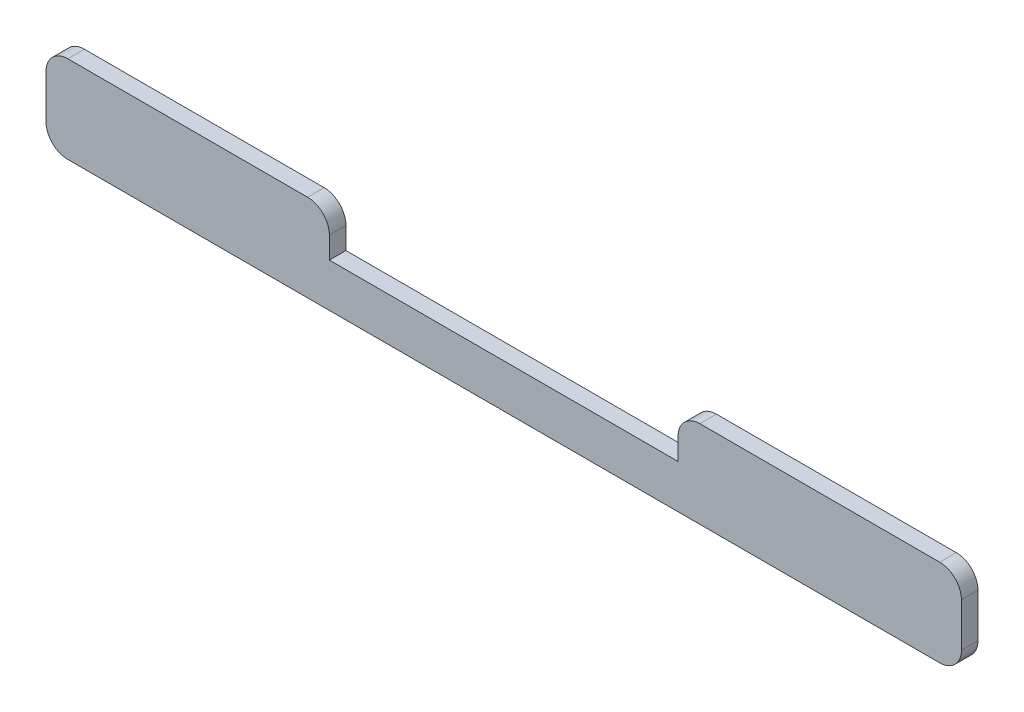
SolidWorks part; units mm, degrees
ref_plane "Front Plane" through (0, 0, 0) normal (0, 0, 1) x (1, 0, 0)
ref_plane "Top Plane" through (0, 0, 0) normal (0, 1, 0) x (1, 0, 0)
ref_plane "Right Plane" through (0, 0, 0) normal (1, 0, 0) x (0, 0, -1)
sketch "Sketch1" plane through (0, 0, 0) normal (0, 0, 1) x (1, 0, 0)
  line L1 (6.35, 0) -> (260.35, 0)
  line L2 (0, 6.35) -> (0, 19.05)
  line L3 (190.5, 25.4) -> (260.35, 25.4)
  line L4 (266.7, 6.35) -> (266.7, 19.05)
  line L5 (82.55, 12.7) -> (184.15, 12.7)
  line L6 (82.55, 12.7) -> (82.55, 19.05)
  line L7 (6.35, 25.4) -> (76.2, 25.4)
  line L8 (184.15, 12.7) -> (184.15, 19.05)
  line L11 (82.55, 12.7) -> (82.55, 19.05)
  arc A0 (260.35, 25.4) -> (266.7, 19.05) centre (260.35, 19.05) cw
  arc A1 (266.7, 6.35) -> (260.35, 0) centre (260.35, 6.35) cw
  arc A2 (0, 6.35) -> (6.35, 0) centre (6.35, 6.35) ccw
  arc A3 (6.35, 25.4) -> (0, 19.05) centre (6.35, 19.05) ccw
  arc A4 (190.5, 25.4) -> (184.15, 19.05) centre (190.5, 19.05) ccw
  arc A5 (76.2, 25.4) -> (82.55, 19.05) centre (76.2, 19.05) cw
  point P7 (266.7, 25.4)
  point P10 (266.7, 0)
  point P13 (0, 0)
  point P16 (0, 25.4)
  point P17 (133.35, 19.05)
  dimension "D3" = 6.35
  dimension "D4" = 6.35
  dimension "D1" = 266.7
  dimension "D2" = 25.4
  dimension "D5" = 101.6
  dimension "D6" = 133.35
extrude "Boss-Extrude1" add sketch "Sketch1" along normal blind 4.826 contours A5 L7 A3 L2 A2 L1 A1 L4 A0 L3 A4 L8 L5 L6
equation "\"MDF\"= 0.19in"
equation "\"PVCID\" = 2.067in"
equation "\"PVCOD\" = 2.375in"
equation "\"GenDiameter\"= 60mm"
equation "\"GenCutDiameter\" = 1.8in"
equation "\"GenCutDistance\" = 1"
equation "\"TowerHeight\" = 6in"
equation "\"TowerFrontBase\" = 3in"
equation "\"FunnelHeight\" = 1in"
equation "\"FunnelAngle\" = 20"
equation "\"TowerSideBase\" = 3in"
equation "\"TowerPanelLength\" = 2in"
equation "\"TowerPanelLeeway\" = 0.5in"
equation "\"BaseLength\" = 9in"
equation "\"BaseWidth\" = 10in"
equation "\"WheelHoleLength\" = 3.25in"
equation "\"WheelHoleWidth\" = 26mm"
equation "\"WheelHoleFromBack\" = 1.5in"
equation "\"DropLength\" = 1in"
equation "\"DropWidth\" = 8.5in"
equation "\"BumperWidth\" = 2in"
equation "\"SmallHexDiameter\" = 0.185in"
equation "\"SmallHexHeight\" = 0.701in"
equation "\"ScrewSize\" = 0.106in"
equation "\"BigHexDiameter\" = 0.251in"
equation "\"BigHexHeight\" = 0.374in"
equation "\"PCBThickness\" = 0.066in"
equation "\"ConnectorHeight\" = 0.517in"
equation "\"BoardHeight\" = 0.583in"
equation "\"UnoStackHeight\" = 1.351in"
equation "\"UnoStackWidth\" = 3.053in"
equation "\"UnoStackLength\" = 3.152in"
equation "\"HBridgeWidth\" = 1.797in"
equation "\"HBridgeLength\" = 2.236in"
equation "\"DSWidth\" = 1.820in"
equation "\"DSLength\" = 1.833in"
equation "\"StepperWidth\" = 1.799in"
equation "\"StepperLength\" = 2.248in"
equation "\"ULNWidth\" = 1.304in"
equation "\"ULNLength\" = 1.545in"
equation "\"VSwitchHeight\" = 0.392in"
equation "\"VSwitchWidth\" = 0.637in"
equation "\"VSwitchLength\" = 1.097in"
equation "\"SkateWheelDiameter\" = 80mm"
equation "\"SkateWheelThickness\" = 24mm"
equation "\"BaseDistance\" = 3in"
equation "\"DummyVar\" = 2in"
equation "\"D1@Boss-Extrude1\"=\"MDF\""
